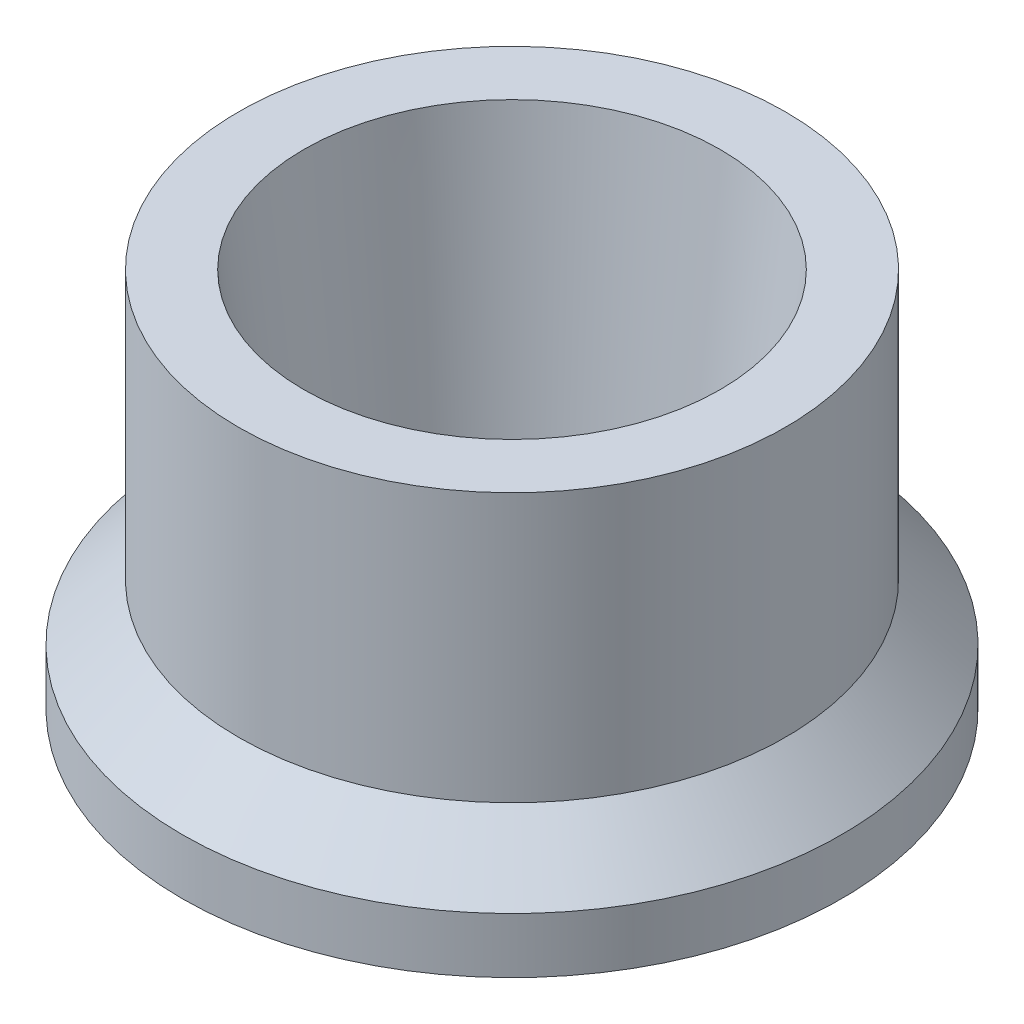
SolidWorks part; units mm, degrees
material "1060 Alloy"
ref_plane "Front" through (0, 0, 0) normal (0, 0, 1) x (1, 0, 0)
ref_plane "Top" through (0, 0, 0) normal (0, 1, 0) x (1, 0, 0)
ref_plane "Right" through (0, 0, 0) normal (1, 0, 0) x (0, 0, -1)
sketch "Sketch1" plane through (0, 0, 0) normal (0, 0, 1) x (1, 0, 0)
  line L0 (3.048, 0) -> (3.81, 6.9596)
  line L1 (50, 0) -> (-50, 0) construction
  line L2 (3.81, 6.9596) -> (5.0038, 6.9596)
  line L3 (5.0038, 6.9596) -> (5.0038, 2.0447)
  line L4 (5.0038, 2.0447) -> (6.0325, 1.016)
  line L5 (6.0325, 1.016) -> (6.0325, 0)
  line L6 (6.0325, 0) -> (3.048, 0)
  line L7 (0, 0) -> (0, 6.9596) construction
  line L8 (0, -50) -> (0, 50) construction
  point P13 (3.81, 6.9596)
  point P14 (2.8182, 6.9596)
  point P15 (0, 0)
  dimension "D1" = 3.048
  dimension "D2" = 6.0325
  dimension "D3" = 5.0038
  dimension "D4" = 6.9596
  dimension "D5" = 1.016
  dimension "D6" = 45
  dimension "D7" = 3.81
revolve "Revolve1" add sketch "Sketch1" angle 360 about L7
